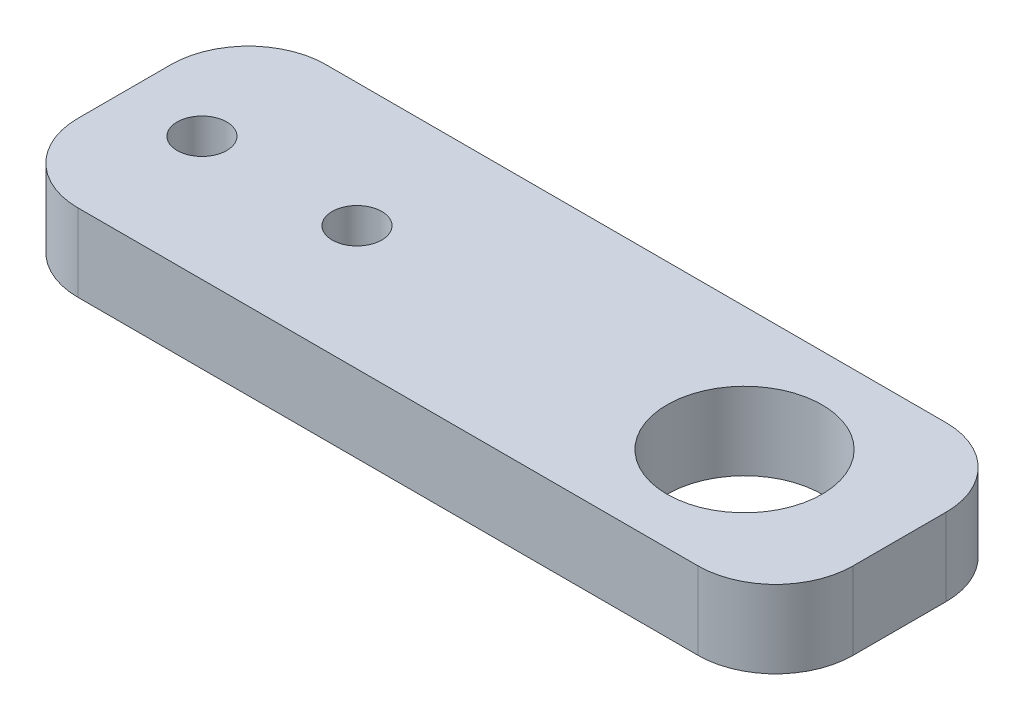
SolidWorks part; units mm, degrees
ref_plane "Front Plane" through (0, 0, 0) normal (0, 0, 1) x (1, 0, 0)
ref_plane "Top Plane" through (0, 0, 0) normal (0, 1, 0) x (1, 0, 0)
ref_plane "Right Plane" through (0, 0, 0) normal (1, 0, 0) x (0, 0, -1)
sketch "Sketch1" plane through (0, 0, 0) normal (0, 1, 0) x (1, 0, 0)
  line L0 (0, 8) -> (50, 8) construction
  line L1 (0, 0) -> (50, 0)
  line L2 (0, 0) -> (0, 16)
  line L3 (0, 16) -> (50, 16)
  line L4 (50, 0) -> (50, 16)
  circle A0 centre (40, 8) radius 5
  circle A1 centre (5, 8) radius 1.6
  circle A2 centre (15, 8) radius 1.6
  point P13 (27.1898, 1.7436)
  point P14 (9.1406, 1.7436)
  point P15 (2.6082, 1.7436)
  dimension "D2" = 3.2
  dimension "D3" = 10
  dimension "D1" = 50
  dimension "D4" = 16
  dimension "D5" = 10
  dimension "D6" = 5
  dimension "D7" = 10
extrude "Boss-Extrude1" add sketch "Sketch1" along normal blind 5
fillet "Fillet1" radius 5 4 edges at (50, 2.5, 0) (50, 2.5, -16) (0, 2.5, 0) (0, 2.5, -16)
